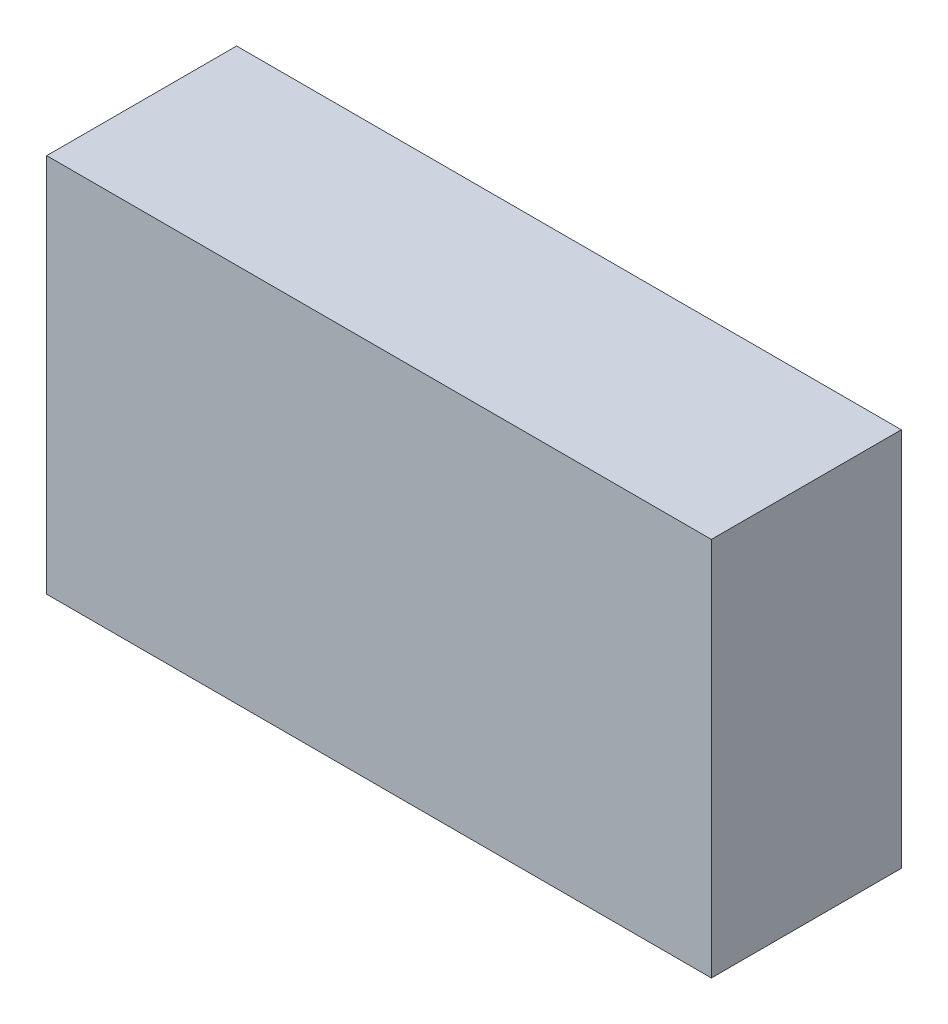
SolidWorks part; units mm, degrees
ref_plane "Alzado" through (0, 0, 0) normal (0, 0, 1) x (1, 0, 0)
ref_plane "Planta" through (0, 0, 0) normal (0, 1, 0) x (1, 0, 0)
ref_plane "Vista lateral" through (0, 0, 0) normal (1, 0, 0) x (0, 0, -1)
sketch "Croquis1" plane through (0, 0, 0) normal (0, 0, 1) x (1, 0, 0)
  line L1 (-1.8363, 1999.2281) -> (3498.1637, 1999.2281)
  line L2 (-1.8363, 1999.2281) -> (-1.8363, -0.7719)
  line L3 (-1.8363, -0.7719) -> (3498.1637, -0.7719)
  line L4 (3498.1637, 1999.2281) -> (3498.1637, -0.7719)
  point P4 (-2471.8075, -364.8004)
  dimension "D1" = 2000
  dimension "D2" = 3500
extrude "Saliente-Extruir1" add sketch "Croquis1" along normal blind 1000
